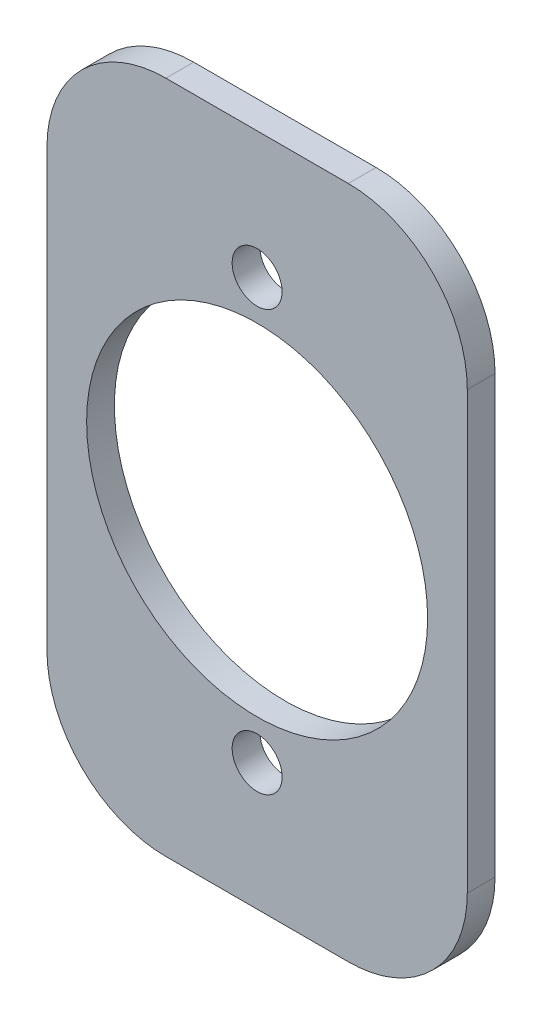
SolidWorks part; units mm, degrees
ref_plane "Front Plane" through (0, 0, 0) normal (0, 0, 1) x (1, 0, 0)
ref_plane "Top Plane" through (0, 0, 0) normal (0, 1, 0) x (1, 0, 0)
ref_plane "Right Plane" through (0, 0, 0) normal (1, 0, 0) x (0, 0, -1)
sketch "Sketch1" plane through (0, 0, 0) normal (0, 0, 1) x (1, 0, 0)
  line L5 (25, 65) -> (-25, 65)
  line L6 (33, 57) -> (33, -57)
  line L7 (25, -65) -> (-25, -65)
  line L8 (-33, 57) -> (-33, -57)
  line L9 (33, 65) -> (-33, -65) construction
  line L10 (33, -65) -> (-33, 65) construction
  arc A4 (-33, -57) -> (-25, -65) centre (-25, -57) ccw
  arc A5 (25, -65) -> (33, -57) centre (25, -57) ccw
  arc A6 (33, 57) -> (25, 65) centre (25, 57) ccw
  arc A7 (-33, 57) -> (-25, 65) centre (-25, 57) cw
  point P0 (0, 0)
  dimension "D1" = 130
  dimension "D2" = 8
  dimension "D3" = 50
extrude "Boss-Extrude1" add sketch "Sketch1" along normal blind 5
sketch "Sketch4" plane through (0, 0, 0) normal (0, 0, -1) x (-1, 0, 0)
  line L1 (-26.5, -42.5) -> (26.5, -42.5)
  line L2 (-26.5, -42.5) -> (-26.5, 42.5)
  line L3 (-26.5, 42.5) -> (26.5, 42.5)
  line L4 (26.5, -42.5) -> (26.5, 42.5)
  line L5 (-26.5, -42.5) -> (26.5, 42.5) construction
  line L6 (-26.5, 42.5) -> (26.5, -42.5) construction
  point P0 (0, 0)
  dimension "D1" = 85
  dimension "D2" = 53
extrude "Boss-Extrude2" add sketch "Sketch4" along normal blind 3.5
sketch "Sketch2" plane through (0, 0, 5) normal (0, 0, 1) x (1, 0, 0)
  circle A0 centre (0, 0) radius 21.5
  dimension "D1" = 43
extrude "Cut-Extrude1" cut sketch "Sketch2" against normal through all
sketch "Sketch3" plane through (0, 0, 5) normal (0, 0, 1) x (1, 0, 0)
  line L0 (0, 26.5) -> (0, -26.5) construction
  circle A0 centre (0, 26.5) radius 3.15
  circle A1 centre (0, -26.5) radius 3.15
  point P3 (0, 0)
  dimension "D2" = 6.3
  dimension "D1" = 53
extrude "Cut-Extrude2" cut sketch "Sketch3" against normal through all
sketch "Sketch16" plane through (0, 0, 0) normal (0, 0, -1) x (-1, 0, 0)
  line L1 (-26.5, 42.5) -> (26.5, 42.5)
  line L2 (-26.5, 42.5) -> (-26.5, -42.5)
  line L3 (-26.5, -42.5) -> (26.5, -42.5)
  line L4 (26.5, 42.5) -> (26.5, -42.5)
  line L5 (-40.0582, 69.876) -> (42.0159, 69.876)
  line L6 (-40.0582, 69.876) -> (-40.0582, -70.1772)
  line L7 (-40.0582, -70.1772) -> (42.0159, -70.1772)
  line L8 (42.0159, 69.876) -> (42.0159, -70.1772)
extrude "lazy cut" cut sketch "Sketch16" against normal through all
fillet "Fillet1" radius 15 4 edges at (-26.5, -42.5, 0.75) (26.5, -42.5, 0.75) (26.5, 42.5, 0.75) (-26.5, 42.5, 0.75)
sketch "Sketch17" plane through (0, 42.5, 0) normal (0, 1, 0) x (1, 0, 0)
  line L0 (26.5, 3.5) -> (26.5, -5) construction
  line L1 (-26.5, -5) -> (26.5, -5)
  line L2 (-26.5, -5) -> (-26.5, 0)
  line L3 (-26.5, 0) -> (26.5, 0)
  line L4 (26.5, -5) -> (26.5, 0)
  line L5 (26.5, 3.5) -> (11.5, 3.5) construction
  dimension "D1" = 3.5
extrude "Cut-Extrude7" cut sketch "Sketch17" against normal through all
sketch "Sketch12" plane through (0, 0, 5) normal (0, 0, 1) x (1, 0, 0)
  line L6 (0, 0) -> (0, 59.75) construction
  line L7 (0, 59.75) -> (-27.75, 59.75) construction
  line L8 (0, 0) -> (-27.75, 0) construction
  line L9 (-27.75, 0) -> (-27.75, 59.75) construction
  line L10 (-27.75, 59.75) -> (-30.6569, 59.446) construction
  circle A0 centre (-27.75, 59.75) radius 2.9
  circle A1 centre (27.75, 59.75) radius 2.9
  circle A2 centre (-27.75, -59.75) radius 2.9
  circle A3 centre (27.75, -59.75) radius 2.9
  circle A4 centre (-27.75, 59.75) radius 3 construction
  dimension "D3" = 5.8
  dimension "D4" = 6
  dimension "D1" = 27.75
  dimension "D2" = 59.75
extrude "Cut-Extrude3" cut sketch "Sketch12" against normal blind 3
sketch "Sketch13" plane through (0, 0, 2) normal (0, 0, 1) x (1, 0, 0)
  line L0 (0, 0) -> (0, 65) construction
  line L1 (25, 65) -> (-25, 65) construction
  line L2 (0, 0) -> (-27.75, 0) construction
  circle A0 centre (-27.75, 59.75) radius 1.75
  circle A1 centre (27.75, 59.75) radius 1.75
  circle A2 centre (27.75, -59.75) radius 1.75
  circle A3 centre (-27.75, -59.75) radius 1.75
  dimension "D1" = 3.5
extrude "Cut-Extrude4" cut sketch "Sketch13" against normal through all
sketch "Sketch14" plane through (0, 0, 5) normal (0, 0, 1) x (1, 0, 0)
  line L0 (5.5, 0) -> (-5.5, 0) construction
  line L1 (-5.5, 26.5) -> (-5.5, -26.5)
  line L3 (5.5, 26.5) -> (5.5, -26.5)
  line L4 (-5.5, -26.5) -> (-3.65, -26.5) construction
  arc A2 (5.5, 26.5) -> (-5.5, 26.5) centre (0, 26.5) ccw
  arc A3 (-5.5, 26.5) -> (5.5, 26.5) centre (0, 26.5) ccw construction
  arc A4 (-5.5, -26.5) -> (5.5, -26.5) centre (0, -26.5) cw construction
  arc A5 (5.5, -26.5) -> (-5.5, -26.5) centre (0, -26.5) cw
  point P7 (0, 0)
  dimension "D2" = 11
extrude "Cut-Extrude5" cut sketch "Sketch14" against normal blind 3 contours L3 A5 L1 A2
sketch "Sketch15" plane through (0, 0, 5) normal (0, 0, 1) x (1, 0, 0)
  line L1 (-2.5, 65) -> (-2.5, 31.399)
  line L2 (25, 65) -> (-25, 65) construction
  line L3 (0, 0) -> (-33, 0) construction
  line L4 (-33, 57) -> (-33, -57) construction
  line L5 (0, 65) -> (0, 0) construction
  line L6 (-27.75, 13.75) -> (-20.8791, 13.75)
  line L7 (-2.5, 65) -> (2.5, 65)
  line L8 (-21.75, 59.75) -> (-6.75, 59.75)
  line L9 (-27.75, 53.75) -> (-27.75, 13.75)
  line L10 (-6.75, 59.75) -> (-6.75, 24.0715)
  line L11 (2.5, 65) -> (2.5, 31.399)
  line L12 (27.75, 13.75) -> (20.8791, 13.75)
  line L13 (6.75, 59.75) -> (6.75, 24.0715)
  line L14 (21.75, 59.75) -> (6.75, 59.75)
  line L15 (27.75, 53.75) -> (27.75, 13.75)
  line L16 (27.75, -53.75) -> (27.75, -13.75)
  line L17 (21.75, -59.75) -> (6.75, -59.75)
  line L18 (6.75, -59.75) -> (6.75, -24.0715)
  line L19 (27.75, -13.75) -> (20.8791, -13.75)
  line L20 (2.5, -65) -> (2.5, -31.399)
  line L21 (-6.75, -59.75) -> (-6.75, -24.0715)
  line L22 (-27.75, -53.75) -> (-27.75, -13.75)
  line L23 (-21.75, -59.75) -> (-6.75, -59.75)
  line L24 (-2.5, -65) -> (2.5, -65)
  line L25 (-27.75, -13.75) -> (-20.8791, -13.75)
  line L26 (-2.5, -65) -> (-2.5, -31.399)
  arc A3 (-6.75, 24.0715) -> (-20.8791, 13.75) centre (0, 0) ccw
  arc A4 (-27.75, 53.75) -> (-21.75, 59.75) centre (-27.75, 59.75) ccw
  arc A5 (2.5, 31.399) -> (-2.5, 31.399) centre (0, 26.5) ccw
  arc A6 (6.75, 24.0715) -> (20.8791, 13.75) centre (0, 0) cw
  arc A7 (27.75, 53.75) -> (21.75, 59.75) centre (27.75, 59.75) cw
  arc A8 (-21.75, -59.75) -> (-27.75, -53.75) centre (-27.75, -59.75) cw construction
  arc A9 (27.75, -53.75) -> (21.75, -59.75) centre (27.75, -59.75) ccw
  arc A10 (6.75, -24.0715) -> (20.8791, -13.75) centre (0, 0) ccw
  arc A11 (-21.75, 59.75) -> (-27.75, 53.75) centre (-27.75, 59.75) ccw construction
  arc A12 (2.5, -31.399) -> (-2.5, -31.399) centre (0, -26.5) cw
  arc A13 (-27.75, -53.75) -> (-21.75, -59.75) centre (-27.75, -59.75) cw
  arc A14 (-6.75, -24.0715) -> (-20.8791, -13.75) centre (0, 0) cw
  dimension "D1" = 50
  dimension "D2" = 15
  dimension "D4" = 12
  dimension "D3" = 2.5
  dimension "D5" = 40
extrude "Cut-Extrude6" cut sketch "Sketch15" against normal blind 1.5
